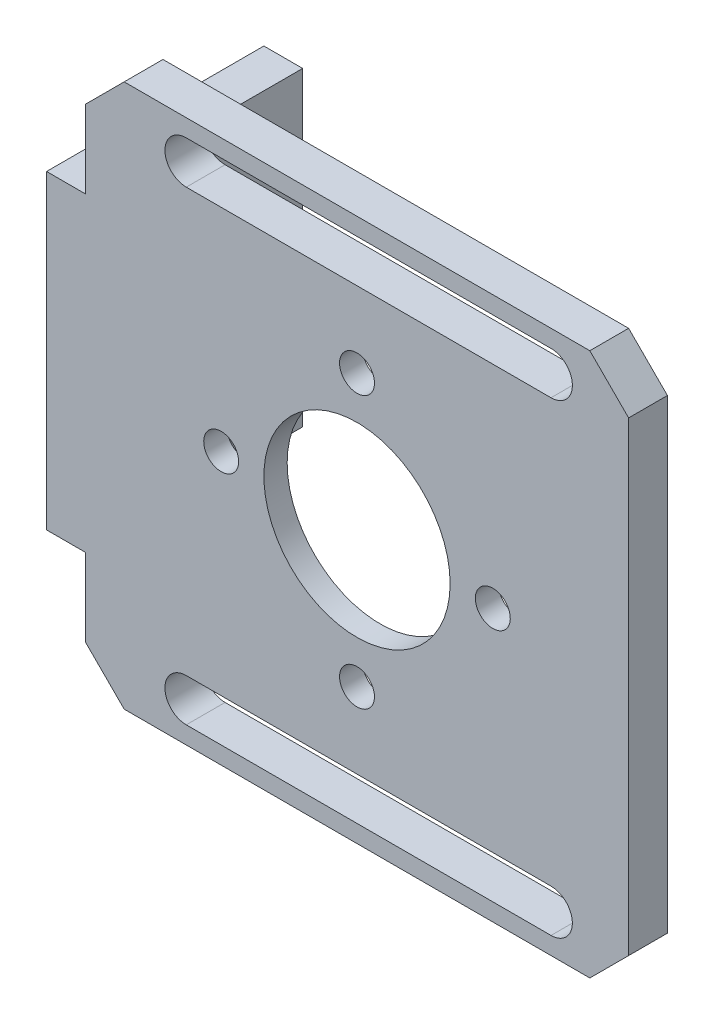
SolidWorks part; units mm, degrees
material "Alliage 1060"
ref_plane "Plan de face" through (0, 0, 0) normal (0, 0, 1) x (1, 0, 0)
ref_plane "Plan de dessus" through (0, 0, 0) normal (0, 1, 0) x (1, 0, 0)
ref_plane "Plan de droite" through (0, 0, 0) normal (1, 0, 0) x (0, 0, -1)
sketch "Esquisse1" plane through (0, 0, 0) normal (0, 0, 1) x (1, 0, 0)
  line L0 (50.2549, 0) -> (-45.9898, 0) construction
  line L1 (-35, 35) -> (35, 35)
  line L2 (-35, 35) -> (-35, -35)
  line L3 (-35, -35) -> (35, -35)
  line L4 (35, 35) -> (35, -35)
  line L5 (-22, 32.75) -> (25, 32.75)
  line L6 (-22, -27.25) -> (25, -27.25)
  line L7 (-22, 27.25) -> (25, 27.25)
  line L8 (-22, -32.75) -> (25, -32.75)
  arc A0 (-22, 32.75) -> (-22, 27.25) centre (-22, 30) ccw
  arc A1 (25, 32.75) -> (25, 27.25) centre (25, 30) cw
  arc A2 (25, -32.75) -> (25, -27.25) centre (25, -30) ccw
  arc A3 (-22, -32.75) -> (-22, -27.25) centre (-22, -30) cw
  dimension "D1" = 70
  dimension "D2" = 70
  dimension "D3" = 35
  dimension "D4" = 35
  dimension "D5" = 10
  dimension "D6" = 5.5
  dimension "D7" = 30
  dimension "D8" = 47
extrude "Extrusion1" add sketch "Esquisse1" along normal blind 5
chamfer "Chanfrein1" distance 5 angle 45 4 edges at (-35, 35, 2.5) (-35, -35, 2.5) (35, -35, 2.5) (35, 35, 2.5)
sketch "Esquisse2" plane through (0, 0, 0) normal (0, 0, -1) x (-1, 0, 0)
  line L0 (35, 30) -> (35, -30) construction
  line L1 (35, -20) -> (40, -20)
  line L2 (35, -20) -> (35, 20)
  line L3 (35, 20) -> (40, 20)
  line L4 (40, -20) -> (40, 20)
  dimension "D1" = 5
  dimension "D2" = 20
  dimension "D3" = 40
extrude "Extrusion2" add sketch "Esquisse2" along normal blind 23 and the other way blind 5
sketch "Esquisse3" plane through (-35, 0, 0) normal (1, 0, 0) x (0, 0, -1)
  line L0 (0, -30) -> (0, 30) construction
  circle A0 centre (14, 0) radius 3
  dimension "D1" = 6
  dimension "D2" = 14
extrude "Enlèv. mat.-Extru.1" cut sketch "Esquisse3" against normal through all
sketch "Esquisse4" plane through (0, 0, 5) normal (0, 0, 1) x (1, 0, 0)
  circle A0 centre (0, 0) radius 12
  dimension "D1" = 24
extrude "Enlèv. mat.-Extru.2" cut sketch "Esquisse4" against normal through all
sketch "Esquisse5" plane through (0, 0, 0) normal (0, 0, -1) x (-1, 0, 0)
  circle A0 centre (0, 0) radius 23.5
  dimension "D1" = 47
extrude "Enlèv. mat.-Extru.3" cut sketch "Esquisse5" against normal blind 2
sketch "Esquisse6" plane through (0, 0, 5) normal (0, 0, 1) x (1, 0, 0)
  circle A0 centre (0, -17.5) radius 2.25
  dimension "D1" = 4.5
  dimension "D2" = 17.5
extrude "Enlèv. mat.-Extru.4" cut sketch "Esquisse6" against normal through all
pattern_circular "Répétition circulaire1" count 4 every 90 about axis through (0, 0, 0) along (0, 0, 1) of "Enlèv. mat.-Extru.4"
